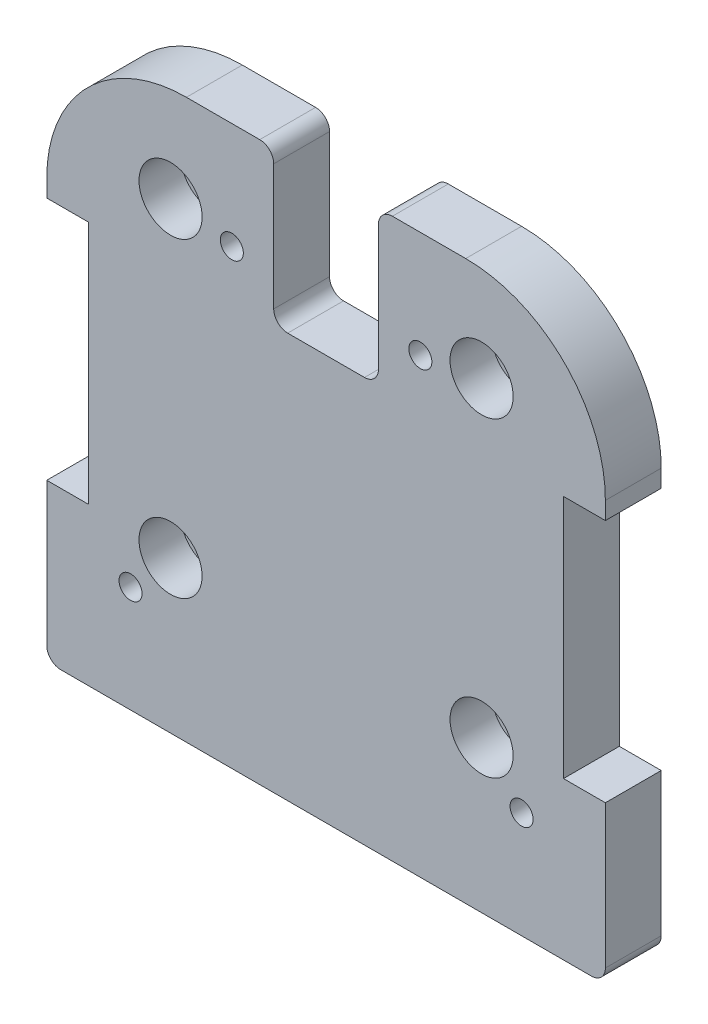
SolidWorks part; units mm, degrees
ref_plane "前视基准面" through (0, 0, 0) normal (0, 0, 1) x (1, 0, 0)
ref_plane "上视基准面" through (0, 0, 0) normal (0, 1, 0) x (1, 0, 0)
ref_plane "右视基准面" through (0, 0, 0) normal (1, 0, 0) x (0, 0, -1)
sketch "草图1" plane through (0, 0, 0) normal (0, 0, 1) x (1, 0, 0)
  line L0 (0, 0) -> (0, 36.8895) construction
  line L2 (-40, 40) -> (40, 40)
  line L3 (-40, 40) -> (-40, -40)
  line L4 (-40, -40) -> (40, -40)
  line L5 (40, 40) -> (40, -40)
  dimension "D1" = 80
  dimension "D2" = 80
  dimension "D3" = 40
  dimension "D4" = 40
extrude "凸台-拉伸1" add sketch "草图1" along normal blind 8 contours L2 L5 L4 L3
sketch "草图7" plane through (0, 0, 8) normal (0, 0, 1) x (1, 0, 0)
  line L0 (0, 0) -> (0, 40) construction
  line L1 (-40, 40) -> (40, 40) construction
  line L3 (-7.5, 40) -> (7.5, 40)
  line L4 (-7.5, 40) -> (-7.5, 18)
  line L5 (-7.5, 18) -> (7.5, 18)
  line L6 (7.5, 40) -> (7.5, 18)
  dimension "D1" = 22
  dimension "D2" = 15
  dimension "D3" = 7.5
extrude "切除-拉伸1" cut sketch "草图7" against normal blind 10
sketch "草图2" plane through (0, 0, 8) normal (0, 0, 1) x (1, 0, 0)
  line L0 (0, 0) -> (0, -40) construction
  line L1 (-40, -40) -> (40, -40) construction
  line L2 (-23.6474, -4.5) -> (32.5152, -4.5) construction
  line L3 (-25.0117, -24.5) -> (44.0357, -24.5) construction
  line L4 (-19.0329, -4.5) -> (-17.8955, -4.5)
  line L5 (17.8955, -4.5) -> (19.0329, -4.5)
  line L6 (17.8955, -24.5) -> (19.0329, -24.5)
  line L7 (-19.0329, -24.5) -> (-17.8955, -24.5)
  arc A0 (-17.8955, -4.5) -> (-17.8955, -24.5) centre (0, -14.5) ccw
  arc A1 (-19.0329, -4.5) -> (-19.0329, -24.5) centre (0, -14.5) ccw
  arc A2 (17.8955, -24.5) -> (17.8955, -4.5) centre (0, -14.5) ccw
  arc A3 (19.0329, -24.5) -> (19.0329, -4.5) centre (0, -14.5) ccw
  dimension "D1" = 25.5
  dimension "D2" = 10
  dimension "D4" = 21.5
  dimension "D5" = 20.5
  dimension "D3" = 20
sketch "草图5" plane through (0, 0, 0) normal (0, 0, -1) x (-1, 0, 0)
  line L0 (0, 30) -> (0, -40) construction
  line L2 (40, -40) -> (-40, -40) construction
  point P6 (-13.5, 24.75)
  point P7 (-28, -24.75)
  point P8 (28, -24.75)
  point P9 (13.5, 24.75)
  dimension "D1" = 13.5
  dimension "D2" = 28
  dimension "D3" = 49.5
  dimension "D4" = 24.75
hole_wizard "M4 螺纹孔1" positions "3D草图2" profile "草图6" tap size "M4" standard "GB" end condition up to next
sketch3d "3D草图2"
  point P0 (13.5, 24.75, 0)
  point P3 (-13.5, 24.75, 0)
  point P6 (-28, -24.75, 0)
  point P9 (28, -24.75, 0)
sketch "草图6" plane through (13.5, 24.75, 0) normal (1, 0, 0) x (0, 1, 0)
  line L0 (0, 0) -> (0, 8)
  line L1 (0, 8) -> (1.65, 8)
  line L2 (1.65, 8) -> (1.65, 0.375)
  line L3 (1.65, 0.375) -> (2.025, 0)
  line L5 (2.025, 0) -> (0, 0)
  line L6 (-1.65, 0.375) -> (-2.025, 0) construction
  line L11 (0, -6.35) -> (0, 107.95) construction
  dimension "通孔螺纹孔钻头直径" = 3.3
  dimension "通孔螺纹孔钻头深度" = 8
  dimension "近端锥形沉头孔直径" = 4.05
  dimension "近端锥形沉头孔角度" = 90
cosmetic thread "孔螺蚊线1" parameters "D2"=4
cosmetic thread "孔螺蚊线2" parameters "D2"=4
cosmetic thread "孔螺蚊线3" parameters "D2"=4
cosmetic thread "孔螺蚊线4" parameters "D2"=4
fillet "圆角1" radius 20 2 edges at (40, 40, 4) (-40, 40, 4)
fillet "圆角2" radius 2 6 edges at (40, -40, 4) (-40, -40, 4) (-7.5, 40, 4) (-7.5, 18, 4) (7.5, 18, 4) (7.5, 40, 4)
sketch "草图9" plane through (0, 0, 0) normal (0, 0, 1) x (1, 0, 0)
  line L0 (40, 17.5) -> (34, 17.5)
  line L1 (40, 20) -> (40, -38) construction
  line L2 (34, 17.5) -> (34, -17.5)
  line L3 (40, 17.5) -> (40, -17.5)
  line L4 (0, 0) -> (46.0009, 0) construction
  line L5 (40, -17.5) -> (34, -17.5)
  line L6 (0, 0) -> (0, 43.2165) construction
  line L7 (-40, -17.5) -> (-34, -17.5)
  line L8 (-34, 17.5) -> (-34, -17.5)
  line L9 (-40, 17.5) -> (-34, 17.5)
  line L10 (-40, 17.5) -> (-40, -17.5)
  point P12 (34, 0)
  dimension "D1" = 35
  dimension "D2" = 6
extrude "切除-拉伸2" cut sketch "草图9" along normal blind 11
sketch "草图11" plane through (0, 0, 0) normal (0, 0, 1) x (1, 0, 0)
  line L0 (0, 36.6897) -> (0, -57.9108) construction
  line L1 (0, 30) -> (0, -40) construction
  line L2 (0, 4) -> (-52.3712, 4) construction
  line L3 (0, 4) -> (-36.4685, 40.4685) construction
  circle A0 centre (0, 4) radius 31.5 construction
  circle A1 centre (-22.2739, 26.2739) radius 3
  circle A2 centre (22.2739, 26.2739) radius 3
  circle A3 centre (22.2739, -18.2739) radius 3
  circle A4 centre (-22.2739, -18.2739) radius 3
  point P20 (0, 4)
  dimension "D1" = 63
  dimension "D4" = 6
  dimension "D2" = 4
  dimension "D3" = 45
  dimension "D5" = 4
extrude "切除-拉伸4" cut sketch "草图11" along normal blind 15
sketch "草图12" plane through (0, 0, 0) normal (0, 0, 1) x (1, 0, 0)
  line L0 (0, 23.5521) -> (0, -40.7043) construction
  line L1 (11.5312, 21.34) -> (15.4688, 21.34)
  line L2 (15.4688, 21.34) -> (17.4375, 24.75)
  line L3 (17.4375, 24.75) -> (15.4688, 28.16)
  line L4 (15.4688, 28.16) -> (11.5312, 28.16)
  line L5 (11.5312, 28.16) -> (9.5625, 24.75)
  line L6 (9.5625, 24.75) -> (11.5312, 21.34)
  line L7 (26.0312, -28.16) -> (29.9688, -28.16)
  line L8 (29.9688, -28.16) -> (31.9375, -24.75)
  line L9 (31.9375, -24.75) -> (29.9688, -21.34)
  line L10 (29.9688, -21.34) -> (26.0312, -21.34)
  line L11 (26.0312, -21.34) -> (24.0625, -24.75)
  line L12 (24.0625, -24.75) -> (26.0312, -28.16)
  line L13 (0, 30) -> (0, -40) construction
  line L14 (-24.0625, -24.75) -> (-26.0312, -28.16)
  line L15 (-26.0312, -21.34) -> (-24.0625, -24.75)
  line L16 (-29.9688, -21.34) -> (-26.0312, -21.34)
  line L17 (-31.9375, -24.75) -> (-29.9688, -21.34)
  line L18 (-29.9688, -28.16) -> (-31.9375, -24.75)
  line L19 (-26.0312, -28.16) -> (-29.9688, -28.16)
  line L20 (-9.5625, 24.75) -> (-11.5312, 21.34)
  line L21 (-11.5312, 28.16) -> (-9.5625, 24.75)
  line L22 (-15.4688, 28.16) -> (-11.5312, 28.16)
  line L23 (-17.4375, 24.75) -> (-15.4688, 28.16)
  line L24 (-15.4688, 21.34) -> (-17.4375, 24.75)
  line L25 (-11.5312, 21.34) -> (-15.4688, 21.34)
  circle A0 centre (-28, -24.75) radius 1.65 construction
  circle A1 centre (28, -24.75) radius 1.65 construction
  circle A2 centre (-13.5, 24.75) radius 1.65 construction
  circle A3 centre (13.5, 24.75) radius 1.65 construction
  circle A4 centre (-28, -24.75) radius 1.65 construction
  circle A5 centre (28, -24.75) radius 1.65 construction
  circle A6 centre (-13.5, 24.75) radius 1.65 construction
  circle A7 centre (13.5, 24.75) radius 1.65 construction
  circle A8 centre (13.5, 24.75) radius 3.41 construction
  circle A9 centre (28, -24.75) radius 3.41 construction
  dimension "D1" = 6.82
  dimension "D2" = 6.82
extrude "切除-拉伸5" cut sketch "草图12" along normal blind 3.6
sketch "草图13" plane through (0, 0, 8) normal (0, 0, 1) x (1, 0, 0)
  line L0 (0, 30) -> (0, -52.7857) construction
  circle A0 centre (-22.2739, 26.2739) radius 4.52
  circle A1 centre (-22.2739, -18.2739) radius 4.52
  circle A2 centre (22.2739, -18.2739) radius 4.52
  circle A3 centre (22.2739, 26.2739) radius 4.52
  dimension "D1" = 9.04
  dimension "D2" = 9.04
extrude "切除-拉伸6" cut sketch "草图13" against normal blind 6
